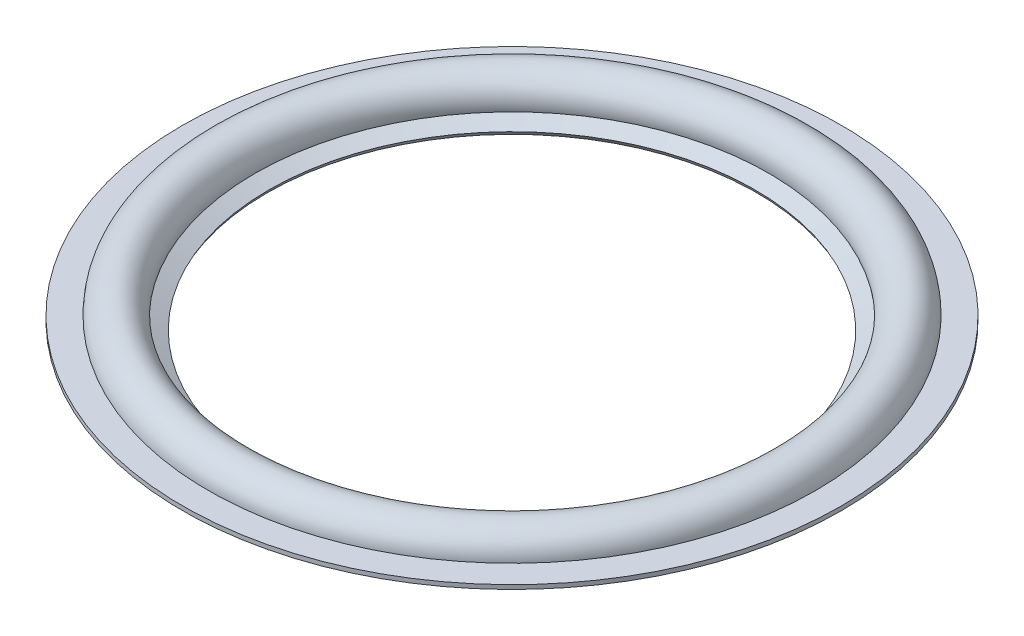
SolidWorks part; units mm, degrees
material "Бутил"
ref_plane "Спереди" through (0, 0, 0) normal (0, 0, 1) x (1, 0, 0)
ref_plane "Сверху" through (0, 0, 0) normal (0, 1, 0) x (1, 0, 0)
ref_plane "Справа" through (0, 0, 0) normal (1, 0, 0) x (0, 0, -1)
sketch "Эскиз1" plane through (0, 0, 0) normal (0, 0, 1) x (1, 0, 0)
  line L0 (-63, 0) -> (-58, 0)
  line L1 (-49.1125, -1) -> (-46.4637, -2.4084)
  line L2 (-63, -0.8) -> (-57.1125, -0.8)
  line L3 (-50.0732, -1.3953) -> (-46.8393, -3.1148)
  line L4 (-63, -0.8) -> (-63, 0)
  line L5 (-46.8393, -3.1148) -> (-46.4637, -2.4084)
  line L6 (0, 0) -> (0, -3.1148) construction
  arc A0 (-58, 0) -> (-49.1125, -1) centre (-53.5, 0) cw
  arc A1 (-57.1125, -0.8) -> (-50.0732, -1.3953) centre (-53.5, 0) cw
  dimension "D3" = 4.5
  dimension "D1" = 63
  dimension "D2" = 5
  dimension "D4" = 3
  dimension "D5" = 1
  dimension "D6" = 28
  dimension "D7" = 0.8
revolve "Повернуть1" add sketch "Эскиз1" angle 360 about L6
fillet "Скругление1" radius 0.5 2 edges at (-50.0732, -1.3953, 0) (-57.1125, -0.8, 0)
